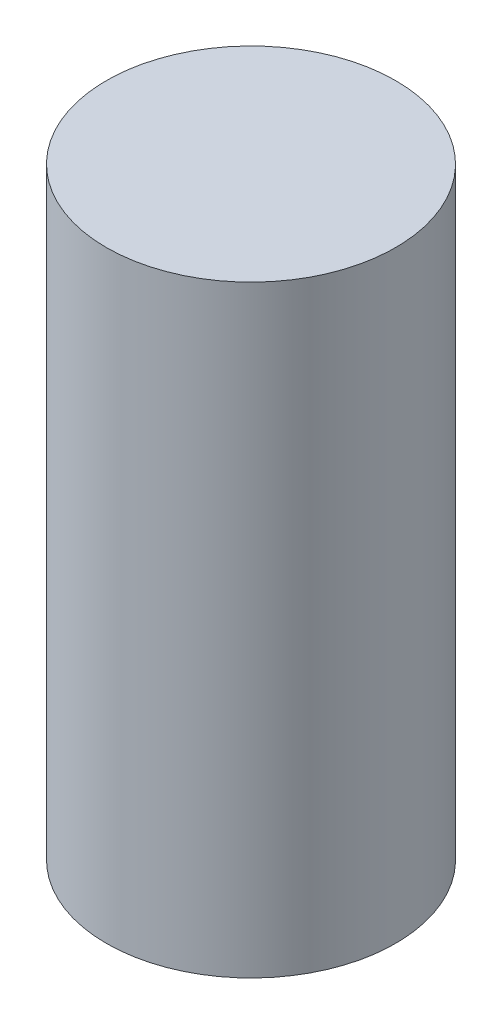
SolidWorks part; units mm, degrees
ref_plane "前视基准面" through (0, 0, 0) normal (0, 0, 1) x (1, 0, 0)
ref_plane "上视基准面" through (0, 0, 0) normal (0, 1, 0) x (1, 0, 0)
ref_plane "右视基准面" through (0, 0, 0) normal (1, 0, 0) x (0, 0, -1)
other "Configuration Table"
sketch "草图1" plane through (0, 0, 0) normal (0, 1, 0) x (1, 0, 0)
  circle A0 centre (0, 0) radius 6
extrude "凸台-拉伸1" add sketch "草图1" along normal blind 25
